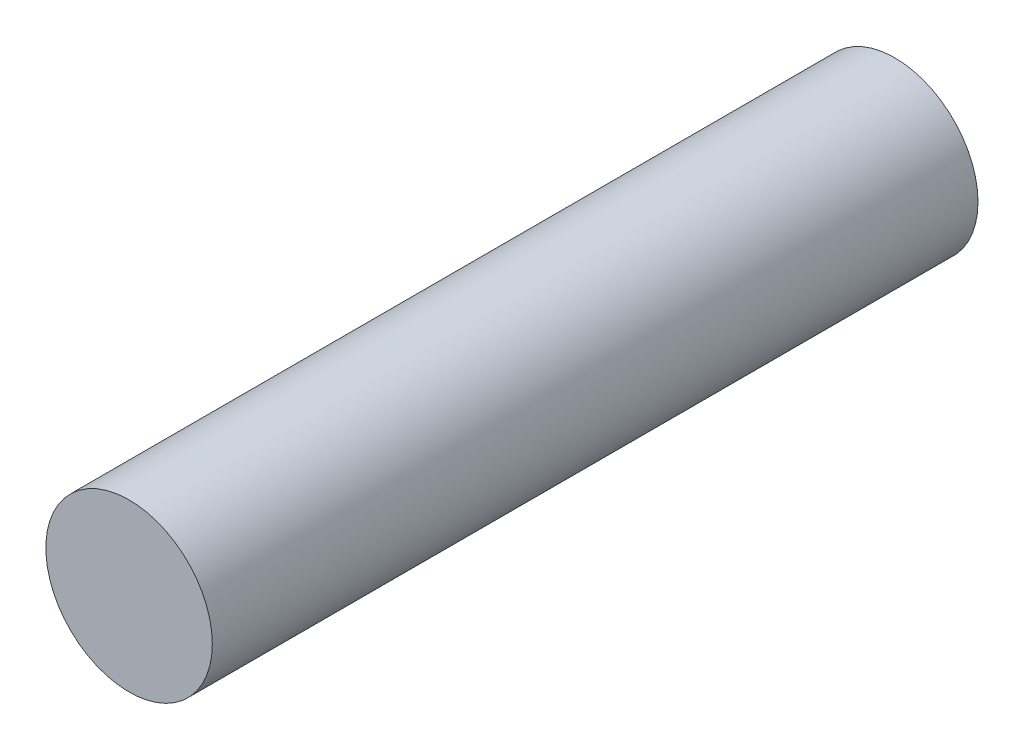
SolidWorks part; units mm, degrees
ref_plane "Front Plane" through (0, 0, 0) normal (0, 0, 1) x (1, 0, 0)
ref_plane "Top Plane" through (0, 0, 0) normal (0, 1, 0) x (1, 0, 0)
ref_plane "Right Plane" through (0, 0, 0) normal (1, 0, 0) x (0, 0, -1)
sketch "Sketch1" plane through (0, 0, 0) normal (0, 0, 1) x (1, 0, 0)
  circle A0 centre (0, 0) radius 2.5
  dimension "D1" = 5
extrude "Boss-Extrude1" add sketch "Sketch1" along normal blind 23
